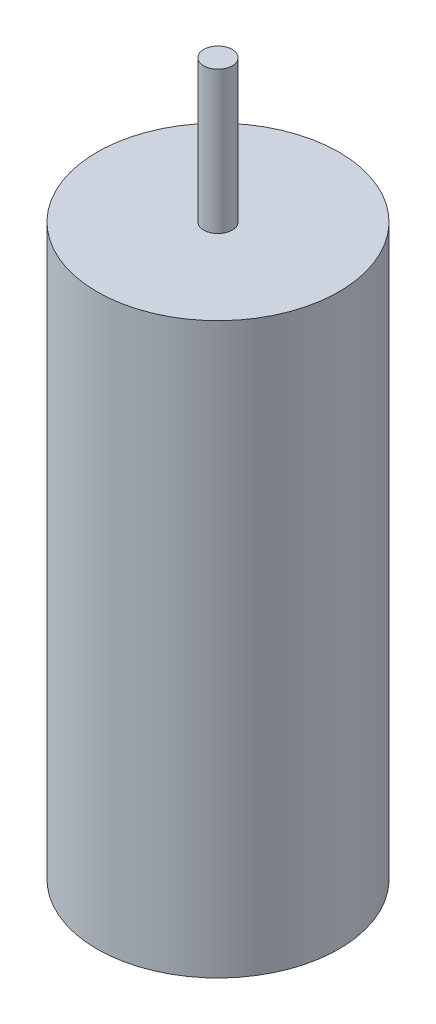
SolidWorks part; units mm, degrees
material "Chrome Stainless Steel"
ref_plane "Front Plane" through (0, 0, 0) normal (0, 0, 1) x (1, 0, 0)
ref_plane "Top Plane" through (0, 0, 0) normal (0, 1, 0) x (1, 0, 0)
ref_plane "Right Plane" through (0, 0, 0) normal (1, 0, 0) x (0, 0, -1)
sketch "Sketch1" plane through (0, 0, 0) normal (0, 1, 0) x (1, 0, 0)
  circle A0 centre (0, 0) radius 4.25
  dimension "D1" = 8.5
extrude "Boss-Extrude1" add sketch "Sketch1" along normal blind 20
sketch "Sketch2" plane through (0, 20, 0) normal (0, 1, 0) x (1, 0, 0)
  circle A0 centre (0, 0) radius 0.5
  dimension "D1" = 1
extrude "Boss-Extrude2" add sketch "Sketch2" along normal blind 5 contours A0
